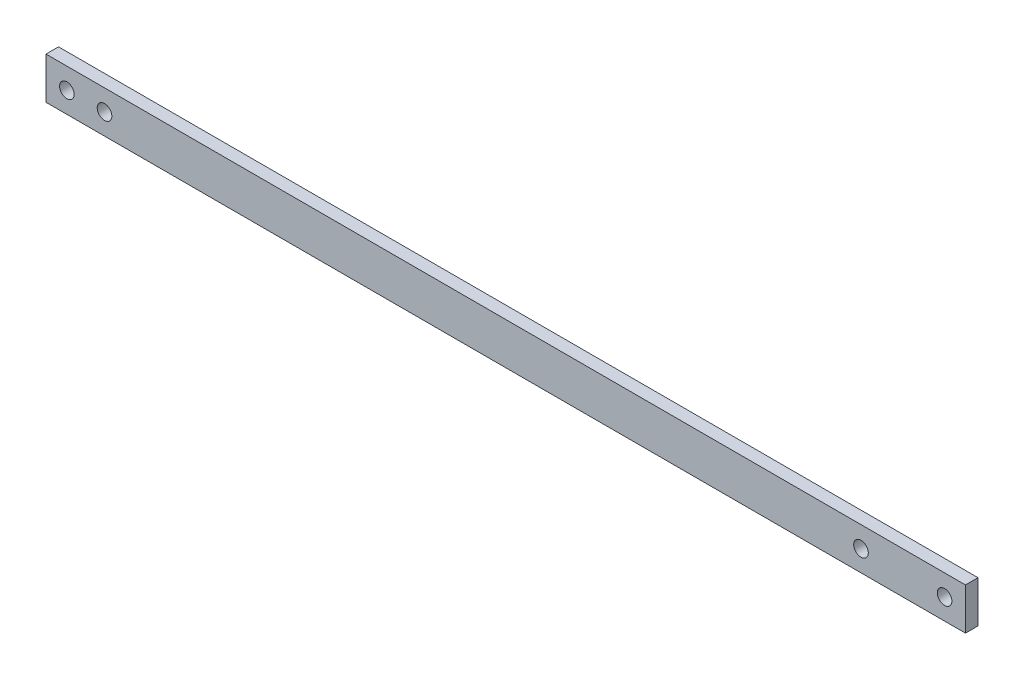
SolidWorks part; units mm, degrees
ref_plane "前视基准面" through (0, 0, 0) normal (0, 0, 1) x (1, 0, 0)
ref_plane "上视基准面" through (0, 0, 0) normal (0, 1, 0) x (1, 0, 0)
ref_plane "右视基准面" through (0, 0, 0) normal (1, 0, 0) x (0, 0, -1)
sketch "草图1" plane through (0, 0, 0) normal (0, 0, 1) x (1, 0, 0)
  line L0 (100, 10) -> (100, 0) construction
  line L1 (0, 0) -> (200, 0)
  line L2 (0, 0) -> (0, 10)
  line L3 (0, 10) -> (200, 10)
  line L4 (200, 0) -> (200, 10)
  line L6 (200, 10) -> (220, 10)
  line L7 (200, 10) -> (200, 0)
  line L8 (200, 0) -> (220, 0)
  line L9 (220, 10) -> (220, 0)
  circle A0 centre (5, 5) radius 1.75
  circle A2 centre (14, 5) radius 1.75
  circle A4 centre (195, 5) radius 1.75
  circle A5 centre (215, 5) radius 1.75
  dimension "D3" = 3.5
  dimension "D4" = 5
  dimension "D5" = 5
  dimension "D6" = 3.5
  dimension "D7" = 9
  dimension "D8" = 5
  dimension "D9" = 3.5
  dimension "D10" = 20
  dimension "D11" = 5
  dimension "D12" = 5
  dimension "D1" = 200
  dimension "D2" = 10
extrude "凸台-拉伸1" add sketch "草图1" along normal blind 3 contours L0 L3 L2 L1 A0 A2 | L3 L0 L1 L4 A4 | L9 L6 L4 L8 A5
